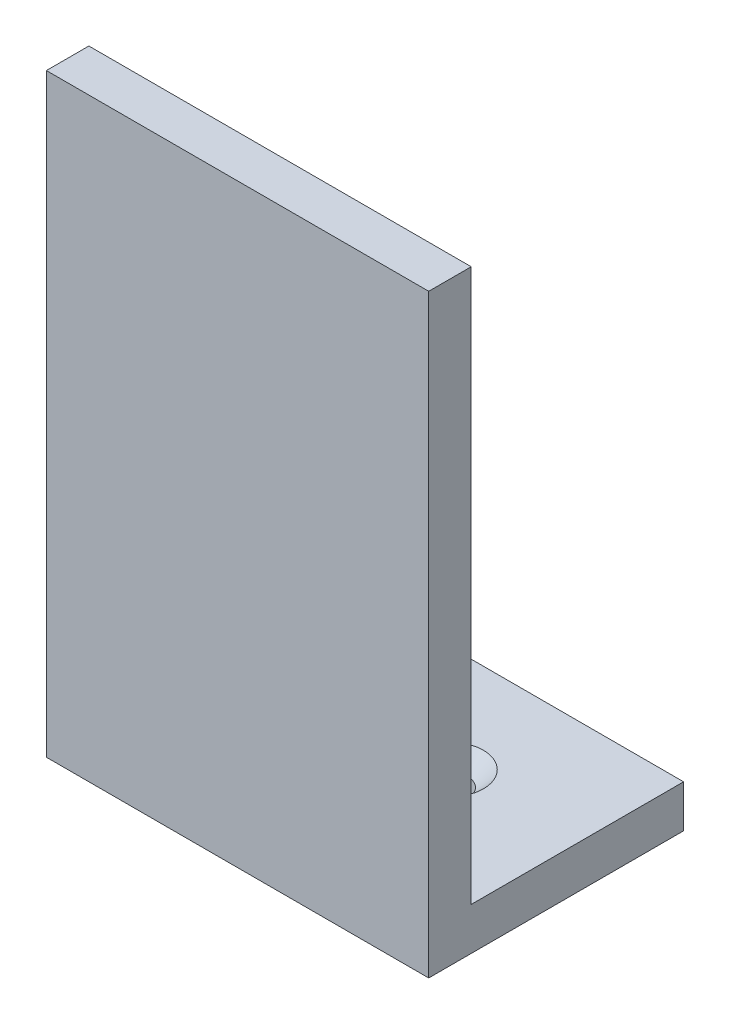
SolidWorks part; units mm, degrees
ref_plane "Płaszczyzna przednia" through (0, 0, 0) normal (0, 0, 1) x (1, 0, 0)
ref_plane "Płaszczyzna górna" through (0, 0, 0) normal (0, 1, 0) x (1, 0, 0)
ref_plane "Płaszczyzna prawa" through (0, 0, 0) normal (1, 0, 0) x (0, 0, -1)
sketch "Sketch1" plane through (0, 0, 0) normal (0, 0, 1) x (1, 0, 0)
  line L1 (-18, 28) -> (18, 28)
  line L2 (-18, 28) -> (-18, -28)
  line L3 (-18, -28) -> (18, -28)
  line L4 (18, 28) -> (18, -28)
  line L5 (-18, 28) -> (18, -28) construction
  line L6 (-18, -28) -> (18, 28) construction
  point P4 (0, 0)
  dimension "D1" = 56
  dimension "D2" = 36
extrude "Boss-Extrude1" add sketch "Sketch1" along normal blind 4
sketch "Sketch2" plane through (0, 0, 0) normal (0, 0, -1) x (-1, 0, 0)
  line L0 (-18, -28) -> (18, -28)
  line L1 (18, -28) -> (18, -24)
  line L2 (18, 28) -> (18, -28) construction
  line L3 (18, -24) -> (-18, -24)
  line L4 (-18, -28) -> (-18, 28) construction
  line L5 (-18, -24) -> (-18, -28)
  point P4 (0, 0)
  dimension "D1" = 4
extrude "Boss-Extrude2" add sketch "Sketch2" along normal blind 20 contours L3 L5 L0 L1
sketch "Sketch8" plane through (0, -24, 0) normal (0, 1, 0) x (1, 0, 0)
  line L0 (-18, 20) -> (18, 0) construction
  line L1 (-18, 0) -> (18, 20) construction
  line L2 (-18, 10) -> (18, 10) construction
  line L3 (-18, 20) -> (-18, 0) construction
  line L4 (18, 20) -> (18, 0) construction
  line L5 (-6, 20) -> (-6, 0) construction
  line L6 (-18, 20) -> (18, 20) construction
  line L7 (18, 0) -> (-18, 0) construction
  line L8 (6, 20) -> (6, 0) construction
  line L9 (-18, 20) -> (-6, 20) construction
  line L10 (-6, 20) -> (6, 20) construction
  line L11 (6, 20) -> (18, 20) construction
  point P24 (-6, 10)
  point P26 (6, 10)
hole_wizard "CSK for M3 Countersunk Flat Head Screw1" positions "Sketch8" profile "Sketch9" countersink size "M3" standard "DIN" end condition up to next
sketch "Sketch9" plane through (6, -24, -10) normal (1, 0, 0) x (0, 0, 1)
  line L0 (0, 0) -> (0, 4)
  line L1 (0, 4) -> (1.7, 4)
  line L2 (1.7, 4) -> (1.7, 1.45)
  line L3 (1.7, 1.45) -> (3.15, 0)
  line L5 (3.15, 0) -> (0, 0)
  line L6 (-1.7, 1.45) -> (-3.15, 0) construction
  line L11 (0, -6.35) -> (0, 107.95) construction
  dimension "Thru Hole Dia." = 3.4
  dimension "Thru Hole Depth" = 4
  dimension "Near C'Sink Dia." = 6.3
  dimension "Near C'Sink Angle" = 90
